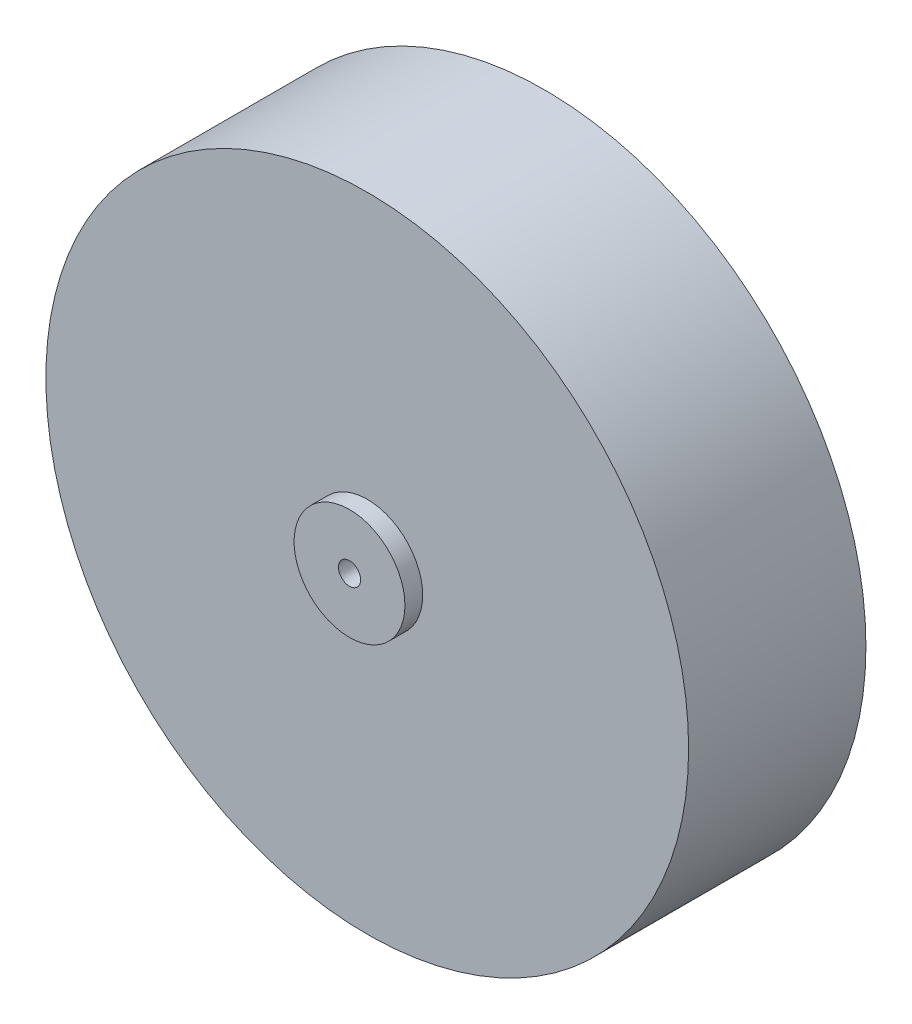
SolidWorks part; units mm, degrees
ref_plane "Front Plane" through (0, 0, 0) normal (0, 0, 1) x (1, 0, 0)
ref_plane "Top Plane" through (0, 0, 0) normal (0, 1, 0) x (1, 0, 0)
ref_plane "Right Plane" through (0, 0, 0) normal (1, 0, 0) x (0, 0, -1)
sketch "Sketch1" plane through (0, 0, 0) normal (0, 0, 1) x (1, 0, 0)
  circle A0 centre (0, 0) radius 72.5
  dimension "D1" = 145
extrude "Boss-Extrude1" add sketch "Sketch1" along normal mid plane 40
sketch "Sketch2" plane through (0, 0, 20) normal (0, 0, 1) x (1, 0, 0)
  circle A0 centre (0, 0) radius 12.5
  dimension "D1" = 25
extrude "Boss-Extrude2" add sketch "Sketch2" along normal blind 4
mirror "Mirror1" about plane through (0, 0, 0) normal (0, 0, 1) of "Boss-Extrude2"
sketch "KeySketch" plane through (6.6247, 1.2697, 24) normal (0, 0, 1) x (1, 0, 0)
  line L0 (-6.6247, -3.7697) -> (-6.6247, 2.2303) construction
  line L1 (-9.1247, -1.2697) -> (-4.1247, -1.2697) construction
  arc A0 (-7.6247, 1.0216) -> (-5.6247, 1.0216) centre (-6.6247, -1.2697) ccw
  circle A1 centre (-6.6247, -1.2697) radius 12.5 construction
  arc A2 (-7.6247, 1.0216) -> (-5.6247, 1.0216) centre (-6.6247, -1.2697) cw
  point P10 (-6.6247, 2.2303)
  dimension "Diameter" = 5
extrude "Keyway" cut sketch "KeySketch" against normal through all
other "bore with square keyway - parallel key<1>"
